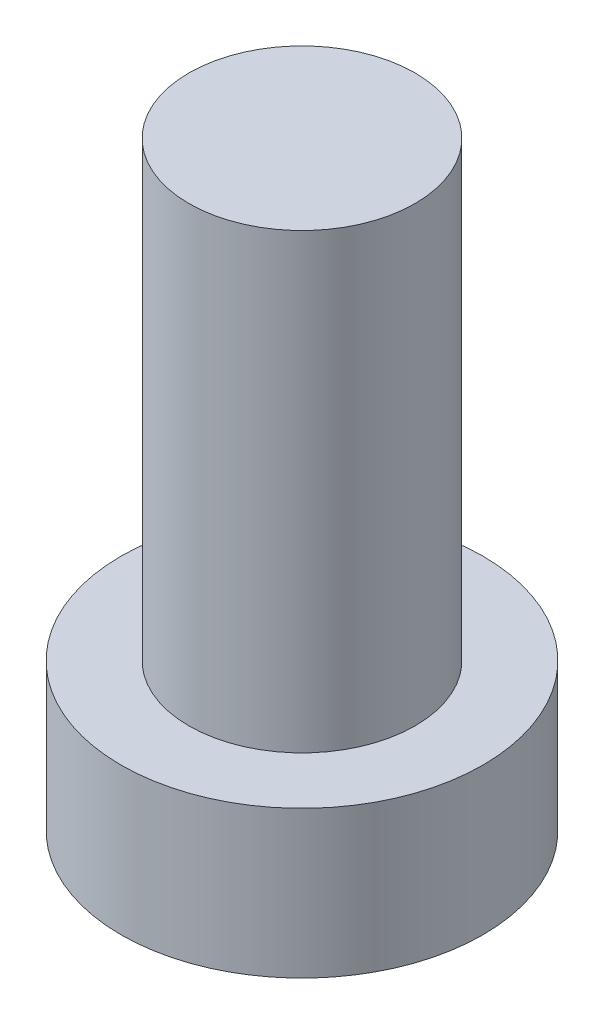
SolidWorks part; units mm, degrees
ref_plane "前视基准面" through (0, 0, 0) normal (0, 0, 1) x (1, 0, 0)
ref_plane "上视基准面" through (0, 0, 0) normal (0, 1, 0) x (1, 0, 0)
ref_plane "右视基准面" through (0, 0, 0) normal (1, 0, 0) x (0, 0, -1)
other "Configuration Table"
sketch "草图1" plane through (0, 0, 0) normal (0, 1, 0) x (1, 0, 0)
  circle A0 centre (0, 0) radius 1.6
  dimension "D1" = 3.2
extrude "凸台-拉伸1" add sketch "草图1" along normal blind 1.3
sketch "草图2" plane through (0, 0, 0) normal (0, 1, 0) x (1, 0, 0)
  circle A0 centre (0, 0) radius 1
extrude "凸台-拉伸2" add sketch "草图2" along normal blind 4 from surface at 1.3 starting at face at (0, 1.3, 1.6)
